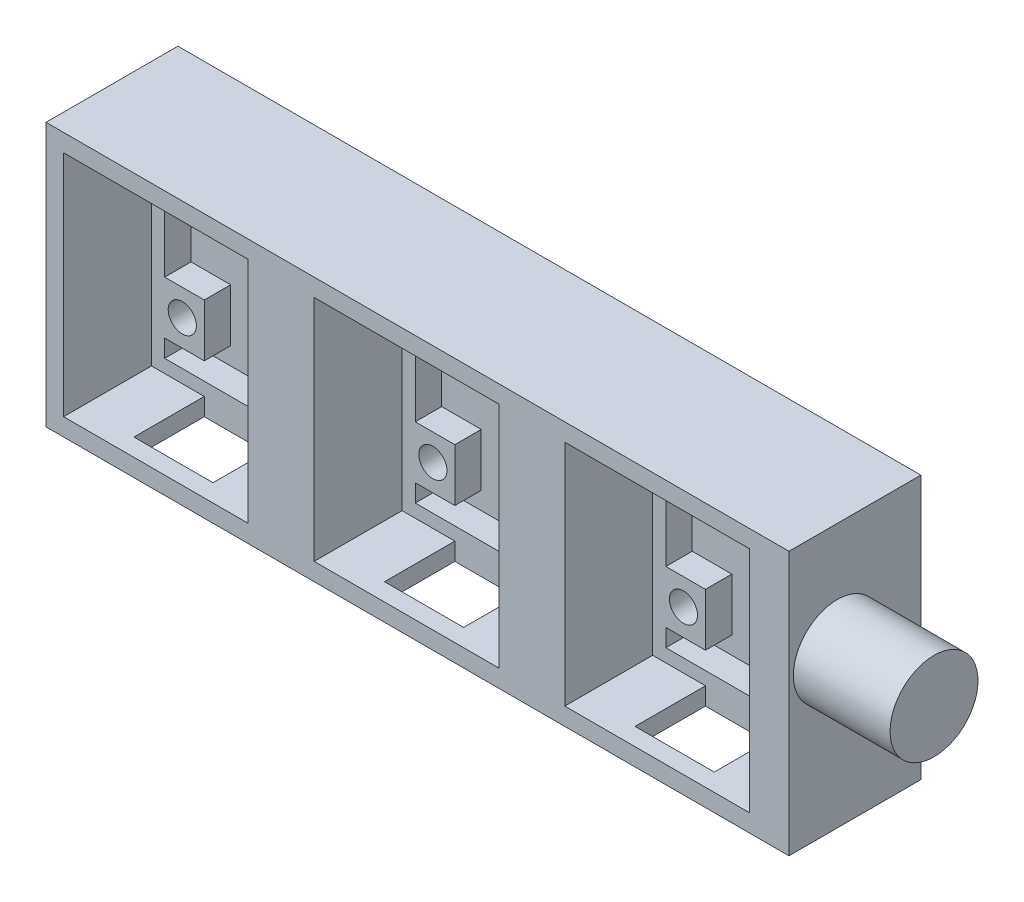
SolidWorks part; units mm, degrees
ref_plane "正面" through (0, 0, 0) normal (0, 0, 1) x (1, 0, 0)
ref_plane "平面" through (0, 0, 0) normal (0, 1, 0) x (1, 0, 0)
ref_plane "右側面" through (0, 0, 0) normal (1, 0, 0) x (0, 0, -1)
sketch "ｽｹｯﾁ1" plane through (0, 0, 0) normal (0, 0, 1) x (1, 0, 0)
  line L1 (-83.9031, 40.6786) -> (0.5969, 40.6786)
  line L2 (-83.9031, 40.6786) -> (-83.9031, 10.6786)
  line L3 (-83.9031, 10.6786) -> (0.5969, 10.6786)
  line L4 (0.5969, 40.6786) -> (0.5969, 10.6786)
  dimension "D1" = 30
  dimension "D2" = 84.5
extrude "ﾎﾞｽ - 押し出し1" add sketch "ｽｹｯﾁ1" along normal blind 15
sketch "ｽｹｯﾁ2" plane through (0, 0, 15) normal (0, 0, 1) x (1, 0, 0)
  line L0 (0.5969, 40.6786) -> (-83.9031, 40.6786) construction
  line L1 (-81.9031, 38.6786) -> (-60.9031, 38.6786)
  line L2 (-81.9031, 38.6786) -> (-81.9031, 12.6786)
  line L3 (-81.9031, 12.6786) -> (-60.9031, 12.6786)
  line L4 (-60.9031, 38.6786) -> (-60.9031, 12.6786)
  line L5 (-83.9031, 10.6786) -> (0.5969, 10.6786) construction
  line L7 (-83.9031, 40.6786) -> (-83.9031, 10.6786) construction
  line L8 (-58.9031, 40.6786) -> (-58.9031, 10.6786) construction
  line L9 (-55.4031, 40.6786) -> (-55.4031, 10.6786) construction
  line L10 (-30.4031, 40.6786) -> (-30.4031, 10.6786) construction
  line L11 (-26.9031, 40.6786) -> (-26.9031, 10.6786) construction
  line L12 (-1.9031, 40.6786) -> (-1.9031, 10.6786) construction
  line L13 (1.5969, 40.6786) -> (1.5969, 10.6786) construction
  line L18 (-53.4031, 38.6786) -> (-32.4031, 38.6786)
  line L19 (-53.4031, 38.6786) -> (-53.4031, 12.6786)
  line L20 (-53.4031, 12.6786) -> (-32.4031, 12.6786)
  line L21 (-32.4031, 38.6786) -> (-32.4031, 12.6786)
  line L22 (-24.9031, 38.6786) -> (-3.9031, 38.6786)
  line L23 (-24.9031, 38.6786) -> (-24.9031, 12.6786)
  line L24 (-24.9031, 12.6786) -> (-3.9031, 12.6786)
  line L25 (-3.9031, 38.6786) -> (-3.9031, 12.6786)
  dimension "D1" = 26
  dimension "D2" = 21
  dimension "D3" = 2
  dimension "D4" = 2
  dimension "D5" = 2
  dimension "D6" = 2
  dimension "D7" = 25
  dimension "D8" = 3.5
  dimension "D9" = 25
  dimension "D10" = 3.5
  dimension "D11" = 25
  dimension "D12" = 3.5
  dimension "D15" = 2
  dimension "D16" = 21
  dimension "D17" = 2
  dimension "D18" = 21
  dimension "D19" = 2
  dimension "D21" = 2
extrude "ｶｯﾄ - 押し出し1" cut sketch "ｽｹｯﾁ2" against normal blind 13
sketch "ｽｹｯﾁ3" plane through (0, 0, 2) normal (0, 0, 1) x (1, 0, 0)
  line L0 (-53.4031, 38.6786) -> (-53.4031, 12.6786) construction
  line L1 (-60.9031, 38.6786) -> (-81.9031, 38.6786)
  line L2 (-60.9031, 38.6786) -> (-60.9031, 12.6786)
  line L3 (-60.9031, 12.6786) -> (-81.9031, 12.6786)
  line L4 (-81.9031, 38.6786) -> (-81.9031, 12.6786)
  line L5 (-80.4031, 37.1786) -> (-62.4031, 37.1786)
  line L6 (-80.4031, 37.1786) -> (-80.4031, 14.1786)
  line L7 (-80.4031, 14.1786) -> (-62.4031, 14.1786)
  line L8 (-62.4031, 37.1786) -> (-62.4031, 14.1786)
  line L9 (-51.9031, 37.1786) -> (-33.9031, 37.1786)
  line L10 (-51.9031, 37.1786) -> (-51.9031, 14.1786)
  line L11 (-51.9031, 14.1786) -> (-33.9031, 14.1786)
  line L12 (-33.9031, 37.1786) -> (-33.9031, 14.1786)
  line L13 (-23.4031, 37.1786) -> (-5.4031, 37.1786)
  line L14 (-23.4031, 37.1786) -> (-23.4031, 14.1786)
  line L15 (-23.4031, 14.1786) -> (-5.4031, 14.1786)
  line L16 (-5.4031, 37.1786) -> (-5.4031, 14.1786)
  line L21 (-24.9031, 38.6786) -> (-24.9031, 12.6786) construction
  line L24 (-53.4031, 38.6786) -> (-32.4031, 38.6786)
  line L25 (-53.4031, 38.6786) -> (-53.4031, 12.6786)
  line L26 (-53.4031, 12.6786) -> (-32.4031, 12.6786)
  line L27 (-32.4031, 38.6786) -> (-32.4031, 12.6786)
  line L28 (-24.9031, 38.6786) -> (-3.9031, 38.6786)
  line L29 (-24.9031, 38.6786) -> (-24.9031, 12.6786)
  line L30 (-24.9031, 12.6786) -> (-3.9031, 12.6786)
  line L31 (-3.9031, 38.6786) -> (-3.9031, 12.6786)
  dimension "D1" = 1.5
  dimension "D2" = 1.5
  dimension "D3" = 1.5
  dimension "D4" = 1.5
  dimension "D5" = 1.5
  dimension "D6" = 1.5
  dimension "D8" = 26
  dimension "D9" = 21
  dimension "D10" = 26
  dimension "D11" = 21
extrude "ﾎﾞｽ - 押し出し2" add sketch "ｽｹｯﾁ3" along normal blind 3
sketch "ｽｹｯﾁ5" plane through (0, 0, 2) normal (0, 0, 1) x (1, 0, 0)
  line L0 (-62.4031, 14.1786) -> (-62.4031, 37.1786) construction
  line L1 (-62.4031, 22.1786) -> (-66.9031, 22.1786)
  line L2 (-62.4031, 22.1786) -> (-62.4031, 16.1786)
  line L3 (-62.4031, 16.1786) -> (-66.9031, 16.1786)
  line L4 (-66.9031, 22.1786) -> (-66.9031, 16.1786)
  line L5 (-51.9031, 37.1786) -> (-51.9031, 14.1786) construction
  line L6 (-81.9031, 12.6786) -> (-60.9031, 12.6786) construction
  line L7 (-80.4031, 37.1786) -> (-80.4031, 14.1786) construction
  line L8 (-80.4031, 22.1786) -> (-75.9031, 22.1786)
  line L9 (-80.4031, 22.1786) -> (-80.4031, 16.1786)
  line L10 (-80.4031, 16.1786) -> (-75.9031, 16.1786)
  line L11 (-75.9031, 22.1786) -> (-75.9031, 16.1786)
  line L12 (-51.9031, 22.1786) -> (-47.4031, 22.1786)
  line L13 (-51.9031, 22.1786) -> (-51.9031, 16.1786)
  line L14 (-51.9031, 16.1786) -> (-47.4031, 16.1786)
  line L15 (-47.4031, 22.1786) -> (-47.4031, 16.1786)
  line L16 (-33.9031, 14.1786) -> (-33.9031, 37.1786) construction
  line L17 (-33.9031, 22.1786) -> (-38.4031, 22.1786)
  line L18 (-33.9031, 22.1786) -> (-33.9031, 16.1786)
  line L19 (-33.9031, 16.1786) -> (-38.4031, 16.1786)
  line L20 (-38.4031, 22.1786) -> (-38.4031, 16.1786)
  line L21 (-23.4031, 37.1786) -> (-23.4031, 14.1786) construction
  line L22 (-23.4031, 22.1786) -> (-18.9031, 22.1786)
  line L23 (-23.4031, 22.1786) -> (-23.4031, 16.1786)
  line L24 (-23.4031, 16.1786) -> (-18.9031, 16.1786)
  line L25 (-18.9031, 22.1786) -> (-18.9031, 16.1786)
  line L26 (-5.4031, 14.1786) -> (-5.4031, 37.1786) construction
  line L27 (-5.4031, 22.1786) -> (-9.9031, 22.1786)
  line L28 (-5.4031, 22.1786) -> (-5.4031, 16.1786)
  line L29 (-5.4031, 16.1786) -> (-9.9031, 16.1786)
  line L30 (-9.9031, 22.1786) -> (-9.9031, 16.1786)
  point P10 (-66.9031, 19.1786)
  point P15 (-75.9031, 19.1786)
  dimension "D1" = 4.5
  dimension "D2" = 6
  dimension "D3" = 6.5
  dimension "D4" = 6.5
extrude "ﾎﾞｽ - 押し出し3" add sketch "ｽｹｯﾁ5" along normal blind 3
sketch "ｽｹｯﾁ6" plane through (0, 0, 5) normal (0, 0, 1) x (1, 0, 0)
  line L0 (-66.9031, 22.1786) -> (-66.9031, 16.1786) construction
  line L1 (-66.9031, 16.1786) -> (-62.4031, 16.1786) construction
  line L2 (-75.9031, 16.1786) -> (-75.9031, 22.1786) construction
  line L3 (-80.4031, 16.1786) -> (-75.9031, 16.1786) construction
  line L4 (-47.4031, 16.1786) -> (-47.4031, 22.1786) construction
  line L5 (-51.9031, 16.1786) -> (-47.4031, 16.1786) construction
  line L6 (-38.4031, 22.1786) -> (-38.4031, 16.1786) construction
  line L7 (-38.4031, 16.1786) -> (-33.9031, 16.1786) construction
  line L8 (-18.9031, 16.1786) -> (-18.9031, 22.1786) construction
  line L9 (-23.4031, 16.1786) -> (-18.9031, 16.1786) construction
  line L10 (-9.9031, 22.1786) -> (-9.9031, 16.1786) construction
  line L11 (-9.9031, 16.1786) -> (-5.4031, 16.1786) construction
  circle A0 centre (-64.4031, 19.1786) radius 1.6
  circle A1 centre (-78.4031, 19.1786) radius 1.6
  circle A2 centre (-49.9031, 19.1786) radius 1.6
  circle A3 centre (-35.9031, 19.1786) radius 1.6
  circle A4 centre (-21.4031, 19.1786) radius 1.6
  circle A5 centre (-7.4031, 19.1786) radius 1.6
  dimension "D1" = 3.2
  dimension "D4" = 2.5
  dimension "D5" = 3
  dimension "D6" = 2.5
  dimension "D2" = 2.5
  dimension "D3" = 3
  dimension "D7" = 3
  dimension "D8" = 2.5
  dimension "D9" = 3
  dimension "D10" = 2.5
  dimension "D11" = 3
  dimension "D12" = 2.5
  dimension "D13" = 3
extrude "ｶｯﾄ - 押し出し2" cut sketch "ｽｹｯﾁ6" against normal through all
sketch "ｽｹｯﾁ7" plane through (0, 12.6786, 0) normal (0, 1, 0) x (1, 0, 0)
  line L0 (-81.9031, -5) -> (-60.9031, -5) construction
  line L1 (-66.9031, -5) -> (-75.9031, -5)
  line L2 (-66.9031, -5) -> (-66.9031, -13)
  line L3 (-66.9031, -13) -> (-75.9031, -13)
  line L4 (-75.9031, -5) -> (-75.9031, -13)
  line L5 (-81.9031, -15) -> (-60.9031, -15) construction
  line L6 (-60.9031, -5) -> (-60.9031, -15) construction
  line L7 (-81.9031, -5) -> (-81.9031, -15) construction
  line L8 (-53.4031, -5) -> (-32.4031, -5) construction
  line L9 (-38.4031, -5) -> (-47.4031, -5)
  line L10 (-38.4031, -5) -> (-38.4031, -13)
  line L11 (-38.4031, -13) -> (-47.4031, -13)
  line L12 (-47.4031, -5) -> (-47.4031, -13)
  line L13 (-24.9031, -5) -> (-3.9031, -5) construction
  line L14 (-9.9031, -5) -> (-18.9031, -5)
  line L15 (-9.9031, -5) -> (-9.9031, -13)
  line L16 (-9.9031, -13) -> (-18.9031, -13)
  line L17 (-18.9031, -5) -> (-18.9031, -13)
  line L23 (-53.4031, -5) -> (-53.4031, -15) construction
  line L24 (-24.9031, -5) -> (-24.9031, -15) construction
  dimension "D1" = 2
  dimension "D2" = 6
  dimension "D3" = 6
  dimension "D4" = 8
  dimension "D5" = 9
  dimension "D6" = 8
  dimension "D7" = 9
  dimension "D10" = 6
  dimension "D11" = 6
extrude "ｶｯﾄ - 押し出し3" cut sketch "ｽｹｯﾁ7" against normal through all
sketch "ｽｹｯﾁ13" plane through (-83.9031, 0, 0) normal (-1, 0, 0) x (0, 0, 1)
  line L0 (0, 40.6786) -> (0, 10.6786) construction
  line L1 (0, 35.5786) -> (1.8, 35.5786)
  line L2 (0, 35.5786) -> (0, 30.7786)
  line L3 (0, 30.7786) -> (1.8, 30.7786)
  line L4 (1.8, 35.5786) -> (1.8, 30.7786)
  line L5 (15, 10.6786) -> (0, 10.6786) construction
  line L6 (0, 20.5786) -> (1.8, 20.5786)
  line L7 (0, 20.5786) -> (0, 15.7786)
  line L8 (0, 15.7786) -> (1.8, 15.7786)
  line L9 (1.8, 20.5786) -> (1.8, 15.7786)
  line L10 (15, 40.6786) -> (0, 40.6786) construction
  point P14 (0.9, 35.5786)
  dimension "D1" = 4.8
  dimension "D2" = 4.8
  dimension "D3" = 1.8
  dimension "D5" = 5.1
  dimension "D6" = 5.1
extrude "ﾎﾞｽ - 押し出し4" add sketch "ｽｹｯﾁ13" along normal blind 3
sketch "ｽｹｯﾁ14" plane through (0.5969, 0, 0) normal (1, 0, 0) x (0, 0, -1)
  line L0 (-15, 10.6786) -> (-15, 40.6786) construction
  line L1 (-15, 10.6786) -> (0, 10.6786) construction
  circle A0 centre (-9.5, 28.1786) radius 5
  dimension "D1" = 10
  dimension "D2" = 5.5
  dimension "D3" = 17.5
extrude "ﾎﾞｽ - 押し出し5" add sketch "ｽｹｯﾁ14" along normal blind 11
